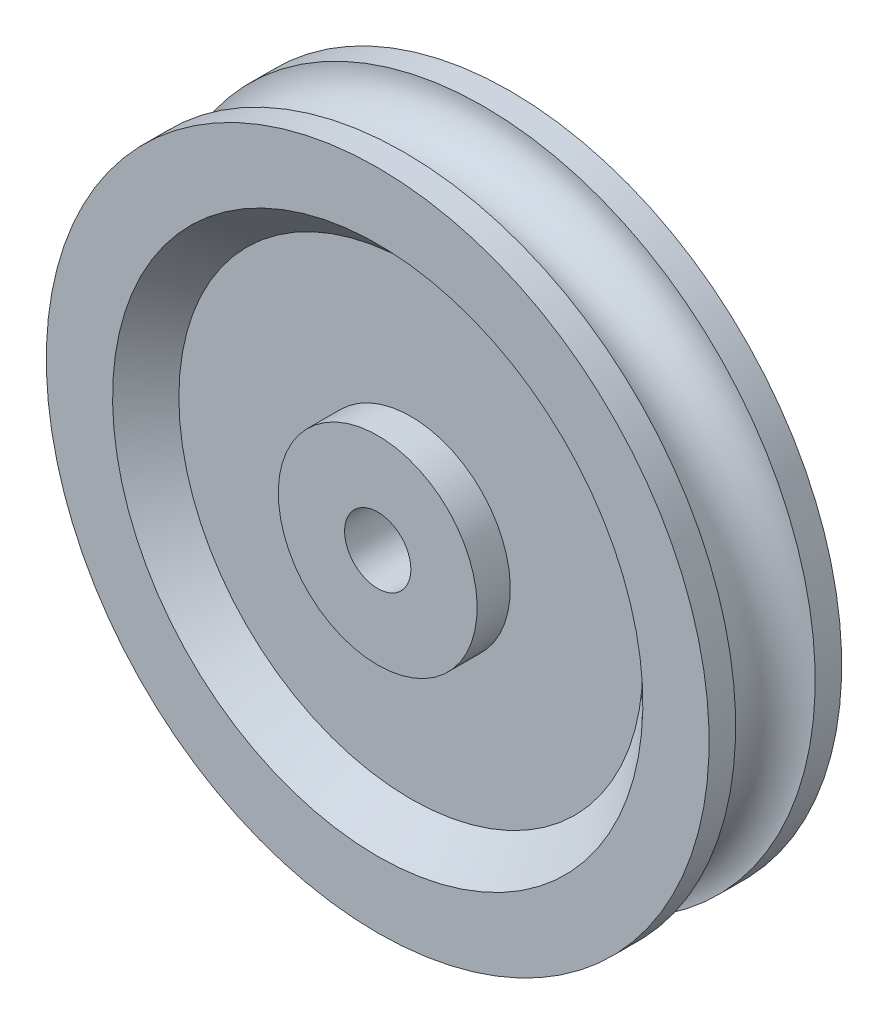
SolidWorks part; units mm, degrees
material "Сталь 3 ГОСТ 535-88"
ref_plane "Спереди" through (0, 0, 0) normal (0, 0, 1) x (1, 0, 0)
ref_plane "Сверху" through (0, 0, 0) normal (0, 1, 0) x (1, 0, 0)
ref_plane "Справа" through (0, 0, 0) normal (1, 0, 0) x (0, 0, -1)
sketch "Эскиз1" plane through (0, 0, 0) normal (1, 0, 0) x (0, 0, -1)
  line L0 (6, 50) -> (10, 50)
  line L2 (-10, 0) -> (-10, 15)
  line L3 (-10, 50) -> (-6, 50)
  line L4 (10, 0) -> (10, 15)
  line L5 (0, 44) -> (0, 0) construction
  line L6 (-10, 0) -> (10, 0) construction
  line L7 (10, 40) -> (5, 35)
  line L8 (5, 35) -> (5, 15)
  line L9 (5, 15) -> (10, 15)
  line L10 (10, 40) -> (10, 50)
  line L11 (-5, 15) -> (-10, 15)
  line L12 (-5, 35) -> (-5, 15)
  line L13 (-10, 40) -> (-5, 35)
  line L14 (-10, 40) -> (-10, 50)
  line L15 (-10, 0) -> (10, 0)
  arc A0 (-6, 50) -> (6, 50) centre (0, 50) ccw
  point P0 (0, 0)
  point P15 (-5, 35.9715)
  dimension "D3" = 12
  dimension "D1" = 20
  dimension "D2" = 100
  dimension "D4" = 15
  dimension "D5" = 10
  dimension "D6" = 5
  dimension "D7" = 10
revolve "Повернуть1" add sketch "Эскиз1" angle 360 about L15
sketch "Эскиз2" plane through (0, 0, 10) normal (0, 0, 1) x (1, 0, 0)
  circle A0 centre (0, 0) radius 5
  dimension "D1" = 10
extrude "Вырез-Вытянуть1" cut sketch "Эскиз2" against normal through all
